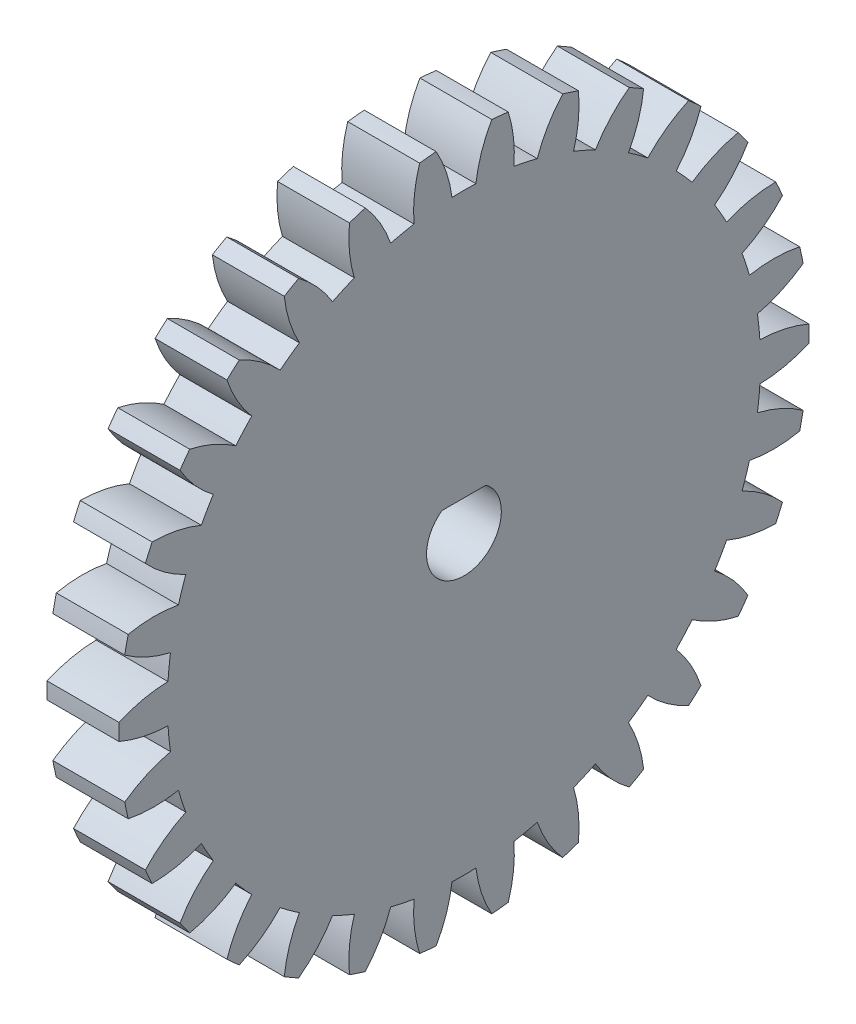
SolidWorks part; units mm, degrees
ref_plane "Plane1" through (0, 0, 0) normal (0, 0, 1) x (1, 0, 0)
ref_plane "Plane2" through (0, 0, 0) normal (0, 1, 0) x (1, 0, 0)
ref_plane "Plane3" through (0, 0, 0) normal (1, 0, 0) x (0, 0, -1)
sketch "HoldingSke" plane through (0, 0, 0) normal (0, 1, 0) x (1, 0, 0)
  line L0 (0, 0) -> (0.5774, -0.3333)
  line L1 (-15, 0) -> (100, 0) construction
  line L2 (0, 0) -> (-2.1039, 2.3779)
  line L3 (0, 0) -> (-11.863, 4.5341)
  line L4 (0, 0) -> (7.479, 4.318)
  line L5 (0, 0) -> (-46.8476, -17.4728)
  line L6 (0, 0) -> (-4.1448, -2.7965)
  line L7 (-2.1039, 2.3779) -> (8.6586, 51.2059)
  line L8 (-76.2, 54.61) -> (-75.9, 54.61)
  line L9 (-67.7845, 28.3722) -> (-49.3413, 33.142)
  line L10 (-76.2, 71.12) -> (104.1128, 71.12)
  line L11 (0, 0) -> (-5, 0)
  line L12 (-76.2, 101.6) -> (-76.147, 101.6)
  line L13 (24.9733, 27.94) -> (52.9518, 28.4284)
  line L14 (24.9733, 27.94) -> (24.9743, 27.94)
  line L15 (24.9733, 27.94) -> (100.4006, 29.5858)
  line L16 (-63.627, -1.5) -> (-12.827, -1.5)
  circle A0 centre (0, 0) radius 1
  circle A1 centre (0, 0) radius 20.624
  circle A2 centre (0, 0) radius 37.5
  circle A3 centre (0, 0) radius 1
  dimension "MHD" = 41.248
  dimension "Hub_dia" = 75
  dimension "Bore" = 2
  dimension "MBD" = 2
  dimension "Num_teeth" = 30
  dimension "Pitch" = 0.6667
  dimension "Overall_len" = 50
  dimension "Show_teeth" = 30
  dimension "Thickness" = 5
  dimension "OAL" = 50.0001
  dimension "T_dim" = 0.3
  dimension "Ap" = 14.5
  dimension "H" = 19.05
  dimension "Pitch_radius" = 180.3128
  dimension "Width" = 5
  dimension "Backlash" = 0.053
  dimension "Addendum_fac" = 1
  dimension "Dedendum_fac" = 1.25
  dimension "Clearance_fac" = 0.25
  dimension "Dedendum_add" = 0.001
  dimension "Module" = 1.5
sketch "BasProSke" plane through (0, 0, 0) normal (0, 1, 0) x (1, 0, 0)
  line L0 (-10, 0) -> (60, 0) construction
  line L1 (0, 0) -> (0, 24)
  line L2 (0, 0) -> (5, 0)
  line L3 (5, 0) -> (5, 24)
  line L4 (5, 24) -> (0, 24)
  dimension "Thickness" = 5
  dimension "Diameter" = 48
revolve "Base-Revolve" add sketch "BasProSke" angle 360 about L0
sketch "TooCutSke" plane through (0, 0, 0) normal (1, 0, 0) x (0, 0, -1)
  line L1 (0, 0) -> (0, 107) construction
  line L2 (0, 0) -> (-1.2703, 22.4641) construction
  line L3 (0, 0) -> (-4.6983, 44.7014) construction
  line L4 (-1.2703, 22.4641) -> (-2.3492, 22.3507) construction
  arc A0 (0.8309, 20.6073) -> (-0.8309, 20.6073) centre (0, 0) ccw
  arc A1 (1.9487, 23.9462) -> (-1.9487, 23.9462) centre (0, 0) ccw
  circle A2 centre (0, 0) radius 22.5 construction
  circle A3 centre (0, 0) radius 21.7833 construction
  arc A4 (-0.8309, 20.6073) -> (-1.9487, 23.9462) centre (-9.7593, 19.4748) ccw
  arc A5 (1.9487, 23.9462) -> (0.8309, 20.6073) centre (9.7593, 19.4748) ccw
  dimension "Root_dia" = 41.248
  dimension "Overcut_dia" = 48.0508
  dimension "Pitch_dia" = 45
  dimension "Base_dia" = 43.5666
  dimension "Flank_rad" = 9
  dimension "Half_ang" = 6
  dimension "Half_CT" = 1.0848
extrude "ToothCut" cut sketch "TooCutSke" along normal through all
fillet "Breaks" [suppressed] radius 0.03
fillet "RootFillets" [suppressed] radius 0.376
pattern_circular "TeethCuts" count 30 every 12 about axis through (-10, 0, 0) along (1, 0, 0) of "ToothCut", "RootFillets", "Breaks"
sketch "HubNeaOneSke" plane through (0, 0, 0) normal (-1, 0, 0) x (0, 0, 1)
  circle A0 centre (0, 0) radius 20.624
  dimension "Diameter" = 41.248
extrude "HubNearOne" [suppressed] add sketch "HubNeaOneSke" along normal blind 45.0001
sketch "HubNeaBotSke" plane through (0, 0, 0) normal (-1, 0, 0) x (0, 0, 1)
  circle A0 centre (0, 0) radius 20.624
  dimension "Diameter" = 41.248
extrude "HubNearBoth" [suppressed] add sketch "HubNeaBotSke" along normal blind 22.5
ref_plane "FarPln" through (5, 0, 0) normal (1, 0, 0) x (0, 0, -1)
sketch "HubFarSke" plane through (5, 0, 0) normal (1, 0, 0) x (0, 0, -1)
  circle A0 centre (0, 0) radius 20.624
  dimension "Diameter" = 41.248
extrude "HubFar" [suppressed] add sketch "HubFarSke" along normal blind 22.5
sketch "BorSke" plane through (0, 0, 0) normal (1, 0, 0) x (0, 0, -1)
  circle A0 centre (0, 0) radius 1
  dimension "Diameter" = 2
extrude "Bore" cut sketch "BorSke" along normal mid plane 100.0001
sketch "KeySke" plane through (0, 0, 0) normal (1, 0, 0) x (0, 0, -1)
  line L0 (-0.4, 0) -> (-0.4, 1.3)
  line L1 (-0.4, 1.3) -> (0.4, 1.3)
  line L2 (0.4, 1.3) -> (0.4, 0)
  line L3 (0, 0) -> (0, 34) construction
  line L4 (-0.4, 0) -> (0.4, 0)
  dimension "Offset" = 1.3
  dimension "Width" = 0.8
extrude "Keyway" [suppressed] cut sketch "KeySke" along normal mid plane 100.0001
pattern_circular "Keyway2" [suppressed] count 2 every 90 about axis through (-10, 0, 0) along (1, 0, 0)
sketch "Schizzo2" plane through (0, 0, 0) normal (-1, 0, 0) x (0, 0, 1)
  line L0 (-1.533, 2.1) -> (1.533, 2.1)
  circle A0 centre (0, 0) radius 2.6
  dimension "D1" = 5.2
  dimension "D2" = 2.1
extrude "Taglio-Estrusione1" cut sketch "Schizzo2" against normal through all and the other way through all contours L0 A0
sketch "Schizzo3" plane through (5, 0, 0) normal (1, 0, 0) x (0, 0, -1)
  circle A0 centre (0, 0) radius 22.5
  dimension "D1" = 45
equation "' \"Module@HoldingSke\" = 6.35"
equation "' \"Num_teeth@HoldingSke\" = 12"
equation "' \"Ap@HoldingSke\" =  20"
equation "' \"Ap@HoldingSke\" = 20"
equation "' \"Width@HoldingSke\" = 0.5 * 25.4"
equation "' \"Hub_dia@HoldingSke\"= 1 * 25.4"
equation "' \"Hub_dia@HoldingSke\" = 1 * 25.4"
equation "' \"Overall_len@HoldingSke\" = 1.0 * 25.4"
equation "' \"Bore@HoldingSke\" = 0.75 * 25.4"
equation "' \"T_dim@HoldingSke\" = 0.1 * 25.4"
equation "' \"Width@KeySke\" = 0.25 * 25.4"
equation "' \"Show_teeth@HoldingSke\" = 13"
equation "' \"Backlash@HoldingSke\" = 0.009 * 25.4"
equation "' \"Addendum_fac@HoldingSke\" = 1.0"
equation "' \"Dedendum_fac@HoldingSke\" = 1.25"
equation "' \"Dedendum_add@HoldingSke\" = 0.00005 * 25.4"
equation "' \"Clearance_fac@HoldingSke\" = 0.25"
equation "\"Pitch@HoldingSke\" = 1 / \"Module@HoldingSke\""
equation "\"Overcut_dia@TooCutSke\" = (\"Num_teeth@HoldingSke\" + 2 * \"Addendum_fac@HoldingSke\") / \"Pitch@HoldingSke\" + 0.002 * 25.4"
equation "\"Pitch_dia@TooCutSke\" = \"Num_teeth@HoldingSke\" / \"Pitch@HoldingSke\""
equation "\"Base_dia@TooCutSke\" = \"Num_teeth@HoldingSke\" / \"Pitch@HoldingSke\" * cos((\"Ap@HoldingSke\"  * 3.14159265 / 180))"
equation "\"Root_dia@TooCutSke\" = (\"Num_teeth@HoldingSke\" + 2) / \"Pitch@HoldingSke\" - 2 * (\"Addendum_fac@HoldingSke\" + \"Dedendum_fac@HoldingSke\") / \"Pitch@HoldingSke\" - \"Dedendum_add@HoldingSke\" * 2"
equation "\"Half_ang@TooCutSke\" = 180 / \"Num_teeth@HoldingSke\""
equation "\"Half_CT@TooCutSke\" = \"Num_teeth@HoldingSke\" / \"Pitch@HoldingSke\" * sin((3.14159265 / 2 / \"Num_teeth@HoldingSke\")) / 2 - 7 * \"Backlash@HoldingSke\" / 4"
equation "\"Flank_rad@TooCutSke\" = \"Num_teeth@HoldingSke\" / \"Pitch@HoldingSke\" / 5"
equation "\"Radius@RootFillets\" = \"Clearance_fac@HoldingSke\" / \"Pitch@HoldingSke\" + \"Dedendum_add@HoldingSke\""
equation "\"Break_rad@Breaks\" = 0.02 / \"Pitch@HoldingSke\""
equation "\"Thickness@HoldingSke\" = \"Width@HoldingSke\""
equation "\"OAL@HoldingSke\" = \"Thickness@HoldingSke\""
equation "\"MHD@HoldingSke\" = (\"Num_teeth@HoldingSke\" + 2) / \"Pitch@HoldingSke\" - 2 * (\"Addendum_fac@HoldingSke\" + \"Dedendum_fac@HoldingSke\")  / \"Pitch@HoldingSke\" - \"Dedendum_add@HoldingSke\" * 2"
equation "\"MBD@HoldingSke\" = (\"Num_teeth@HoldingSke\" + 2) / \"Pitch@HoldingSke\" - 2 * (\"Addendum_fac@HoldingSke\" + \"Dedendum_fac@HoldingSke\")  / \"Pitch@HoldingSke\" - \"Dedendum_add@HoldingSke\" * 2 - 0.002 * 25.4"
equation "\"MHD@HoldingSke\" = ((sgn( \"MHD@HoldingSke\" - \"Hub_dia@HoldingSke\" )-1)*( \"MHD@HoldingSke\" - \"Hub_dia@HoldingSke\" ))/-2+ \"Hub_dia@HoldingSke\""
equation "\"MBD@HoldingSke\" = ((sgn( \"MBD@HoldingSke\" - \"Bore@HoldingSke\" )-1)*( \"MBD@HoldingSke\" - \"Bore@HoldingSke\" ))/-2+ \"Bore@HoldingSke\""
equation "\"OAL@HoldingSke\" = ((sgn( \"OAL@HoldingSke\" - \"Overall_len@HoldingSke\" )+1)*( \"OAL@HoldingSke\" - \"Overall_len@HoldingSke\" ))/2 + \"Overall_len@HoldingSke\" + 0.000002 * 25.4"
equation "\"Num_teeth@TeethCuts\" = int( \"Show_teeth@HoldingSke\" ) + 1"
equation "\"Num_teeth@TeethCuts\" = ((sgn( \"Num_teeth@TeethCuts\" - \"Num_teeth@HoldingSke\" )-1)*( \"Num_teeth@TeethCuts\" - \"Num_teeth@HoldingSke\" ))/-2+ \"Num_teeth@HoldingSke\""
equation "\"Num_teeth@TeethCuts\" = ((sgn( \"Num_teeth@TeethCuts\" - 2.0)+1)*( \"Num_teeth@TeethCuts\" - 2.0))/2 +2.0"
equation "\"Angle@TeethCuts\" = 360.0 / \"Num_teeth@HoldingSke\""
equation "\"Diameter@BasProSke\" = (\"Num_teeth@HoldingSke\" + 2 * \"Addendum_fac@HoldingSke\") / \"Pitch@HoldingSke\""
equation "\"Thickness@BasProSke\"  = \"Thickness@HoldingSke\""
equation "' \"Fillet_rad@BasProSke\" =  \"Thickness@HoldingSke\" * 0.05"
equation "' \"Fillet_rad@BasProSke\" = \"Thickness@HoldingSke\" * 0.05"
equation "\"MHD@HoldingSke\" = ((sgn( \"MHD@HoldingSke\" - \"Root_dia@TooCutSke\" )-1)*( \"MHD@HoldingSke\" - \"Root_dia@TooCutSke\" ))/-2+ \"Root_dia@TooCutSke\""
equation "\"Diameter@HubNeaOneSke\" = \"MHD@HoldingSke\""
equation "\"Length@HubNearOne\" = \"OAL@HoldingSke\" - \"Thickness@BasProSke\""
equation "\"Diameter@HubNeaBotSke\" = \"MHD@HoldingSke\""
equation "\"Length@HubNearBoth\" = ( \"OAL@HoldingSke\" - \"Thickness@BasProSke\" ) / 2.0"
equation "\"Thickness@FarPln\" = \"Thickness@BasProSke\""
equation "\"Diameter@HubFarSke\" = \"MHD@HoldingSke\""
equation "\"Length@HubFar\" = ( \"OAL@HoldingSke\" - \"Thickness@BasProSke\" ) / 2.0"
equation "\"Diameter@BorSke\" = \"MBD@HoldingSke\""
equation "\"D1@Bore\" = \"OAL@HoldingSke\" * 2.0"
equation "\"D1@Keyway\" = \"OAL@HoldingSke\" * 2.0"
equation "\"Offset@KeySke\" = \"T_dim@HoldingSke\" + \"MBD@HoldingSke\" / 2.0"
